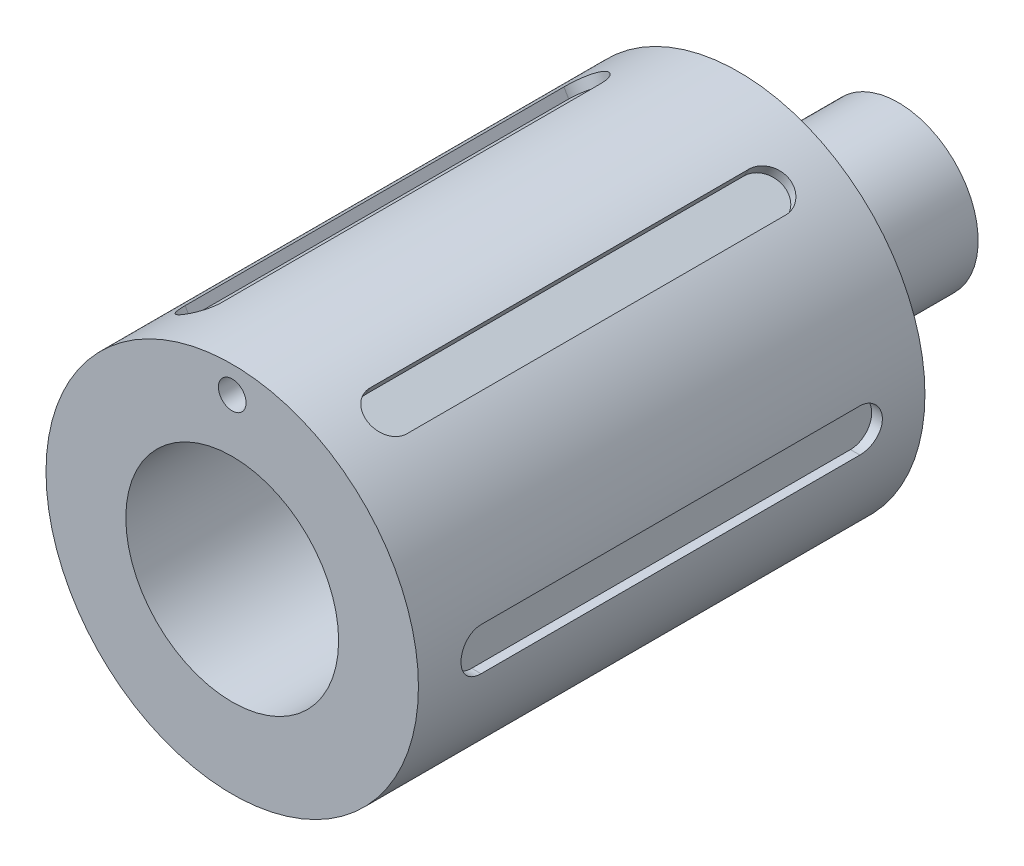
SolidWorks part; units mm, degrees
material "Plain Carbon Steel"
ref_plane "Front Plane" through (0, 0, 0) normal (0, 0, 1) x (1, 0, 0)
ref_plane "Top Plane" through (0, 0, 0) normal (0, 1, 0) x (1, 0, 0)
ref_plane "Right Plane" through (0, 0, 0) normal (1, 0, 0) x (0, 0, -1)
sketch "Sketch1" plane through (0, 0, 0) normal (1, 0, 0) x (0, 0, -1)
  line L0 (0, 0) -> (57.15, 0)
  line L1 (57.15, 0) -> (57.15, 12.7)
  line L2 (57.15, 12.7) -> (79.502, 12.7)
  line L3 (79.502, 12.7) -> (79.502, 3.175)
  line L4 (79.502, 3.175) -> (60.452, 3.175)
  line L5 (60.452, 3.175) -> (60.452, -9.525)
  line L6 (60.452, -9.525) -> (0, -9.525)
  line L7 (0, -9.525) -> (0, 0)
  line L8 (79.502, 12.7) -> (-47.9671, 12.7) construction
  dimension "D1" = 9.525
  dimension "D2" = 19.05
  dimension "D3" = 57.15
  dimension "D4" = 60.452
  dimension "D5" = 9.525
  dimension "D6" = 12.7
revolve "Revolve1" add sketch "Sketch1" angle 360 about L8
hole_wizard "3/8 (0.13) Diameter Hole1" positions "Sketch2" profile "Sketch3" hole size "3/8" standard "ANSI Inch"
sketch "Sketch2" plane through (0, 0, 0) normal (0, 0, 1) x (1, 0, 0)
  point P0 (0, 31.75)
  dimension "D1" = 31.75
sketch "Sketch3" plane through (0, 31.75, 0) normal (1, 0, 0) x (0, -1, 0)
  line L0 (0, 0) -> (0, 16.867)
  line L1 (0, 16.867) -> (1.651, 15.875)
  line L2 (1.651, 15.875) -> (1.651, 0)
  line L5 (1.651, 0) -> (0, 0)
  line L10 (0, 16.867) -> (-1.651, 15.875) construction
  line L11 (0, -6.35) -> (0, 107.95) construction
  dimension "Hole Dia." = 3.302
  dimension "Hole Depth" = 15.875
  dimension "Drill Angle" = 118
ref_plane "Plane1" through (22.225, 0, 0) normal (1, 0, 0) x (0, 0, -1)
sketch "Sketch5" plane through (22.225, 0, 0) normal (1, 0, 0) x (0, 0, -1)
  line L0 (7.62, 12.7) -> (52.832, 12.7) construction
  line L1 (7.62, 15.24) -> (52.832, 15.24)
  line L2 (7.62, 10.16) -> (52.832, 10.16)
  arc A0 (7.62, 15.24) -> (7.62, 10.16) centre (7.62, 12.7) ccw
  arc A1 (52.832, 10.16) -> (52.832, 15.24) centre (52.832, 12.7) ccw
  point P2 (30.226, 12.7)
  point P11 (0, 0)
  dimension "D2" = 2.54
  dimension "D1" = 45.212
extrude "Cut-Extrude1" cut sketch "Sketch5" against normal blind 1.27
pattern_circular "CirPattern1" count 6 over 360 about axis through (0, 12.7, 0) along (0, 0, 1) of "Cut-Extrude1"
